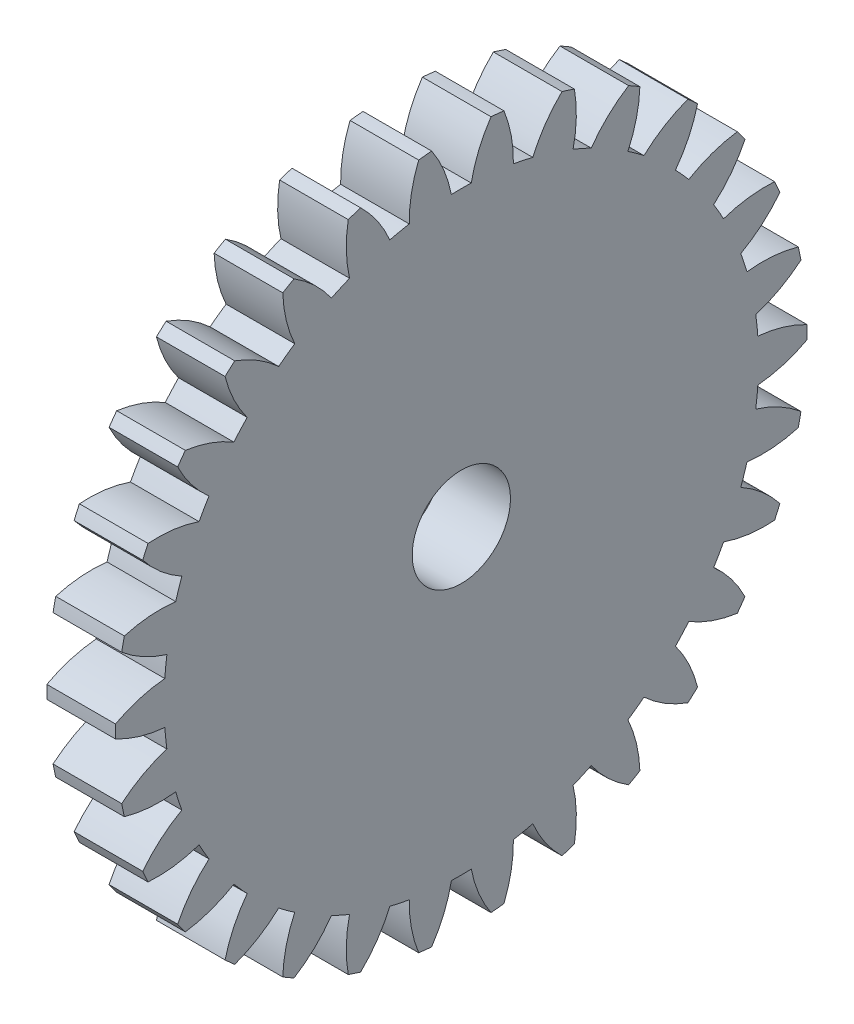
SolidWorks part; units mm, degrees
ref_plane "Plane1" through (0, 0, 0) normal (0, 0, 1) x (1, 0, 0)
ref_plane "Plane2" through (0, 0, 0) normal (0, 1, 0) x (1, 0, 0)
ref_plane "Plane3" through (0, 0, 0) normal (1, 0, 0) x (0, 0, -1)
sketch "HoldingSke" plane through (0, 0, 0) normal (0, 1, 0) x (1, 0, 0)
  line L0 (0, 0) -> (0.433, -0.25)
  line L1 (-15, 0) -> (100, 0) construction
  line L2 (0, 0) -> (-2.1039, 2.3779)
  line L3 (0, 0) -> (-11.863, 4.5341)
  line L4 (0, 0) -> (7.479, 4.318)
  line L5 (0, 0) -> (-46.8476, -17.4728)
  line L6 (0, 0) -> (-5.2639, -3.5516)
  line L7 (-2.1039, 2.3779) -> (8.6586, 51.2059)
  line L8 (-76.2, 54.61) -> (-76.1, 54.61)
  line L9 (-71.009, 38.7566) -> (-53.1078, 45.2721)
  line L10 (-76.2, 71.12) -> (104.1128, 71.12)
  line L11 (0, 0) -> (-6.35, 0)
  line L12 (-76.2, 101.6) -> (-76.133, 101.6)
  line L13 (24.9733, 27.94) -> (52.9518, 28.4284)
  line L14 (24.9733, 27.94) -> (24.9743, 27.94)
  line L15 (24.9733, 27.94) -> (100.4006, 29.5858)
  line L16 (-63.627, -2) -> (-12.827, -2)
  circle A0 centre (0, 0) radius 0.4
  circle A1 centre (0, 0) radius 27.499
  circle A2 centre (0, 0) radius 37.5
  circle A3 centre (0, 0) radius 0.4
  dimension "MHD" = 54.998
  dimension "Hub_dia" = 75
  dimension "Bore" = 0.8
  dimension "MBD" = 0.8
  dimension "Num_teeth" = 30
  dimension "Pitch" = 0.5
  dimension "Overall_len" = 50
  dimension "Show_teeth" = 30
  dimension "Thickness" = 6.35
  dimension "OAL" = 50.0001
  dimension "T_dim" = 0.1
  dimension "Ap" = 20
  dimension "H" = 19.05
  dimension "Pitch_radius" = 180.3128
  dimension "Width" = 6.35
  dimension "Backlash" = 0.067
  dimension "Addendum_fac" = 1
  dimension "Dedendum_fac" = 1.25
  dimension "Clearance_fac" = 0.25
  dimension "Dedendum_add" = 0.001
  dimension "Module" = 2
sketch "BasProSke" plane through (0, 0, 0) normal (0, 1, 0) x (1, 0, 0)
  line L0 (-10, 0) -> (60, 0) construction
  line L1 (0, 0) -> (0, 32)
  line L2 (0, 0) -> (6.35, 0)
  line L3 (6.35, 0) -> (6.35, 32)
  line L4 (6.35, 32) -> (0, 32)
  dimension "Thickness" = 6.35
  dimension "Diameter" = 64
revolve "Base-Revolve" add sketch "BasProSke" angle 360 about L0
sketch "TooCutSke" plane through (0, 0, 0) normal (1, 0, 0) x (0, 0, -1)
  line L1 (0, 0) -> (0, 107) construction
  line L2 (0, 0) -> (-1.6873, 29.9525) construction
  line L3 (0, 0) -> (-6.2643, 59.6013) construction
  line L4 (-1.6873, 29.9525) -> (-3.1322, 29.8007) construction
  arc A0 (0.9186, 27.4837) -> (-0.9186, 27.4837) centre (0, 0) ccw
  arc A1 (2.7618, 31.9061) -> (-2.7618, 31.9061) centre (0, 0) ccw
  circle A2 centre (0, 0) radius 30 construction
  circle A3 centre (0, 0) radius 28.1908 construction
  arc A4 (-0.9186, 27.4837) -> (-2.7618, 31.9061) centre (-12.6936, 25.1712) ccw
  arc A5 (2.7618, 31.9061) -> (0.9186, 27.4837) centre (12.6936, 25.1712) ccw
  dimension "Root_dia" = 54.998
  dimension "Overcut_dia" = 64.0508
  dimension "Pitch_dia" = 60
  dimension "Base_dia" = 56.3816
  dimension "Flank_rad" = 12
  dimension "Half_ang" = 6
  dimension "Half_CT" = 1.4528
extrude "ToothCut" cut sketch "TooCutSke" along normal through all
fillet "Breaks" [suppressed] radius 0.04
fillet "RootFillets" [suppressed] radius 0.501
pattern_circular "TeethCuts" count 30 every 12 about axis through (-10, 0, 0) along (1, 0, 0) of "ToothCut", "RootFillets", "Breaks"
sketch "HubNeaOneSke" plane through (0, 0, 0) normal (-1, 0, 0) x (0, 0, 1)
  circle A0 centre (0, 0) radius 27.499
  dimension "Diameter" = 54.998
extrude "HubNearOne" [suppressed] add sketch "HubNeaOneSke" along normal blind 43.6501
sketch "HubNeaBotSke" plane through (0, 0, 0) normal (-1, 0, 0) x (0, 0, 1)
  circle A0 centre (0, 0) radius 27.499
  dimension "Diameter" = 54.998
extrude "HubNearBoth" [suppressed] add sketch "HubNeaBotSke" along normal blind 21.825
ref_plane "FarPln" through (6.35, 0, 0) normal (1, 0, 0) x (0, 0, -1)
sketch "HubFarSke" plane through (6.35, 0, 0) normal (1, 0, 0) x (0, 0, -1)
  circle A0 centre (0, 0) radius 27.499
  dimension "Diameter" = 54.998
extrude "HubFar" [suppressed] add sketch "HubFarSke" along normal blind 21.825
sketch "BorSke" plane through (0, 0, 0) normal (1, 0, 0) x (0, 0, -1)
  circle A0 centre (0, 0) radius 0.4
  dimension "Diameter" = 0.8
extrude "Bore" cut sketch "BorSke" along normal mid plane 100.0001
sketch "KeySke" plane through (0, 0, 0) normal (1, 0, 0) x (0, 0, -1)
  line L0 (-0.05, 0) -> (-0.05, 0.5)
  line L1 (-0.05, 0.5) -> (0.05, 0.5)
  line L2 (0.05, 0.5) -> (0.05, 0)
  line L3 (0, 0) -> (0, 34) construction
  line L4 (-0.05, 0) -> (0.05, 0)
  dimension "Offset" = 0.5
  dimension "Width" = 0.1
extrude "Keyway" [suppressed] cut sketch "KeySke" along normal mid plane 100.0001
pattern_circular "Keyway2" [suppressed] count 2 every 90 about axis through (-10, 0, 0) along (1, 0, 0)
sketch "Sketch1" plane through (6.35, 0, 0) normal (1, 0, 0) x (0, 0, -1)
  circle A0 centre (0, 0.4) radius 4.5473
  circle A1 centre (0, 0) radius 0.4 construction
extrude "Cut-Extrude1" cut sketch "Sketch1" against normal blind 10
equation "' \"Module@HoldingSke\" = 6.35"
equation "' \"Num_teeth@HoldingSke\" = 12"
equation "' \"Ap@HoldingSke\" =  20"
equation "' \"Ap@HoldingSke\" = 20"
equation "' \"Width@HoldingSke\" = 0.5 * 25.4"
equation "' \"Hub_dia@HoldingSke\"= 1 * 25.4"
equation "' \"Hub_dia@HoldingSke\" = 1 * 25.4"
equation "' \"Overall_len@HoldingSke\" = 1.0 * 25.4"
equation "' \"Bore@HoldingSke\" = 0.75 * 25.4"
equation "' \"T_dim@HoldingSke\" = 0.1 * 25.4"
equation "' \"Width@KeySke\" = 0.25 * 25.4"
equation "' \"Show_teeth@HoldingSke\" = 13"
equation "' \"Backlash@HoldingSke\" = 0.009 * 25.4"
equation "' \"Addendum_fac@HoldingSke\" = 1.0"
equation "' \"Dedendum_fac@HoldingSke\" = 1.25"
equation "' \"Dedendum_add@HoldingSke\" = 0.00005 * 25.4"
equation "' \"Clearance_fac@HoldingSke\" = 0.25"
equation "\"Pitch@HoldingSke\" = 1 / \"Module@HoldingSke\""
equation "\"Overcut_dia@TooCutSke\" = (\"Num_teeth@HoldingSke\" + 2 * \"Addendum_fac@HoldingSke\") / \"Pitch@HoldingSke\" + 0.002 * 25.4"
equation "\"Pitch_dia@TooCutSke\" = \"Num_teeth@HoldingSke\" / \"Pitch@HoldingSke\""
equation "\"Base_dia@TooCutSke\" = \"Num_teeth@HoldingSke\" / \"Pitch@HoldingSke\" * cos((\"Ap@HoldingSke\"  * 3.14159265 / 180))"
equation "\"Root_dia@TooCutSke\" = (\"Num_teeth@HoldingSke\" + 2) / \"Pitch@HoldingSke\" - 2 * (\"Addendum_fac@HoldingSke\" + \"Dedendum_fac@HoldingSke\") / \"Pitch@HoldingSke\" - \"Dedendum_add@HoldingSke\" * 2"
equation "\"Half_ang@TooCutSke\" = 180 / \"Num_teeth@HoldingSke\""
equation "\"Half_CT@TooCutSke\" = \"Num_teeth@HoldingSke\" / \"Pitch@HoldingSke\" * sin((3.14159265 / 2 / \"Num_teeth@HoldingSke\")) / 2 - 7 * \"Backlash@HoldingSke\" / 4"
equation "\"Flank_rad@TooCutSke\" = \"Num_teeth@HoldingSke\" / \"Pitch@HoldingSke\" / 5"
equation "\"Radius@RootFillets\" = \"Clearance_fac@HoldingSke\" / \"Pitch@HoldingSke\" + \"Dedendum_add@HoldingSke\""
equation "\"Break_rad@Breaks\" = 0.02 / \"Pitch@HoldingSke\""
equation "\"Thickness@HoldingSke\" = \"Width@HoldingSke\""
equation "\"OAL@HoldingSke\" = \"Thickness@HoldingSke\""
equation "\"MHD@HoldingSke\" = (\"Num_teeth@HoldingSke\" + 2) / \"Pitch@HoldingSke\" - 2 * (\"Addendum_fac@HoldingSke\" + \"Dedendum_fac@HoldingSke\")  / \"Pitch@HoldingSke\" - \"Dedendum_add@HoldingSke\" * 2"
equation "\"MBD@HoldingSke\" = (\"Num_teeth@HoldingSke\" + 2) / \"Pitch@HoldingSke\" - 2 * (\"Addendum_fac@HoldingSke\" + \"Dedendum_fac@HoldingSke\")  / \"Pitch@HoldingSke\" - \"Dedendum_add@HoldingSke\" * 2 - 0.002 * 25.4"
equation "\"MHD@HoldingSke\" = ((sgn( \"MHD@HoldingSke\" - \"Hub_dia@HoldingSke\" )-1)*( \"MHD@HoldingSke\" - \"Hub_dia@HoldingSke\" ))/-2+ \"Hub_dia@HoldingSke\""
equation "\"MBD@HoldingSke\" = ((sgn( \"MBD@HoldingSke\" - \"Bore@HoldingSke\" )-1)*( \"MBD@HoldingSke\" - \"Bore@HoldingSke\" ))/-2+ \"Bore@HoldingSke\""
equation "\"OAL@HoldingSke\" = ((sgn( \"OAL@HoldingSke\" - \"Overall_len@HoldingSke\" )+1)*( \"OAL@HoldingSke\" - \"Overall_len@HoldingSke\" ))/2 + \"Overall_len@HoldingSke\" + 0.000002 * 25.4"
equation "\"Num_teeth@TeethCuts\" = int( \"Show_teeth@HoldingSke\" ) + 1"
equation "\"Num_teeth@TeethCuts\" = ((sgn( \"Num_teeth@TeethCuts\" - \"Num_teeth@HoldingSke\" )-1)*( \"Num_teeth@TeethCuts\" - \"Num_teeth@HoldingSke\" ))/-2+ \"Num_teeth@HoldingSke\""
equation "\"Num_teeth@TeethCuts\" = ((sgn( \"Num_teeth@TeethCuts\" - 2.0)+1)*( \"Num_teeth@TeethCuts\" - 2.0))/2 +2.0"
equation "\"Angle@TeethCuts\" = 360.0 / \"Num_teeth@HoldingSke\""
equation "\"Diameter@BasProSke\" = (\"Num_teeth@HoldingSke\" + 2 * \"Addendum_fac@HoldingSke\") / \"Pitch@HoldingSke\""
equation "\"Thickness@BasProSke\"  = \"Thickness@HoldingSke\""
equation "' \"Fillet_rad@BasProSke\" =  \"Thickness@HoldingSke\" * 0.05"
equation "' \"Fillet_rad@BasProSke\" = \"Thickness@HoldingSke\" * 0.05"
equation "\"MHD@HoldingSke\" = ((sgn( \"MHD@HoldingSke\" - \"Root_dia@TooCutSke\" )-1)*( \"MHD@HoldingSke\" - \"Root_dia@TooCutSke\" ))/-2+ \"Root_dia@TooCutSke\""
equation "\"Diameter@HubNeaOneSke\" = \"MHD@HoldingSke\""
equation "\"Length@HubNearOne\" = \"OAL@HoldingSke\" - \"Thickness@BasProSke\""
equation "\"Diameter@HubNeaBotSke\" = \"MHD@HoldingSke\""
equation "\"Length@HubNearBoth\" = ( \"OAL@HoldingSke\" - \"Thickness@BasProSke\" ) / 2.0"
equation "\"Thickness@FarPln\" = \"Thickness@BasProSke\""
equation "\"Diameter@HubFarSke\" = \"MHD@HoldingSke\""
equation "\"Length@HubFar\" = ( \"OAL@HoldingSke\" - \"Thickness@BasProSke\" ) / 2.0"
equation "\"Diameter@BorSke\" = \"MBD@HoldingSke\""
equation "\"D1@Bore\" = \"OAL@HoldingSke\" * 2.0"
equation "\"D1@Keyway\" = \"OAL@HoldingSke\" * 2.0"
equation "\"Offset@KeySke\" = \"T_dim@HoldingSke\" + \"MBD@HoldingSke\" / 2.0"
